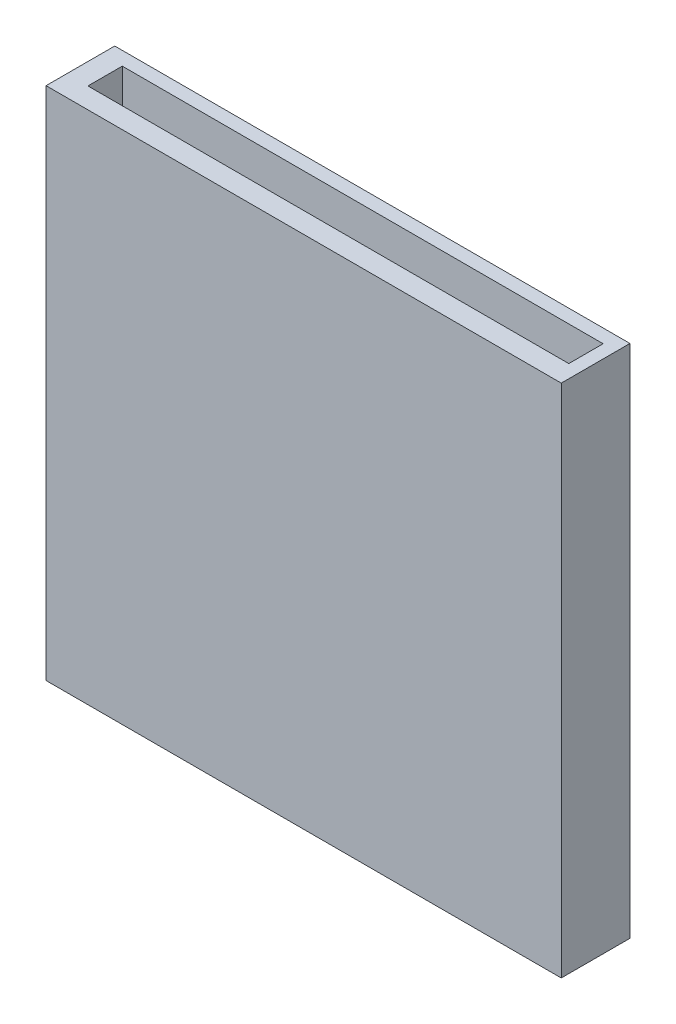
SolidWorks part; units mm, degrees
ref_plane "前视基准面" through (0, 0, 0) normal (0, 0, 1) x (1, 0, 0)
ref_plane "上视基准面" through (0, 0, 0) normal (0, 1, 0) x (1, 0, 0)
ref_plane "右视基准面" through (0, 0, 0) normal (1, 0, 0) x (0, 0, -1)
sketch "草图3" plane through (0, 0, 0) normal (0, 1, 0) x (1, 0, 0)
  line L1 (-68.9842, 26.4973) -> (81.0158, 26.4973)
  line L2 (-68.9842, 26.4973) -> (-68.9842, 6.4973)
  line L3 (-68.9842, 6.4973) -> (81.0158, 6.4973)
  line L4 (81.0158, 26.4973) -> (81.0158, 6.4973)
extrude "凸台-拉伸1" add sketch "草图3" along normal blind 150
sketch "草图4" plane through (0, 150, 0) normal (0, 1, 0) x (1, 0, 0)
  line L1 (-62.8156, 22.5201) -> (77.1844, 22.5201)
  line L2 (-62.8156, 22.5201) -> (-62.8156, 12.5201)
  line L3 (-62.8156, 12.5201) -> (77.1844, 12.5201)
  line L4 (77.1844, 22.5201) -> (77.1844, 12.5201)
extrude "切除-拉伸1" cut sketch "草图4" against normal blind 145
